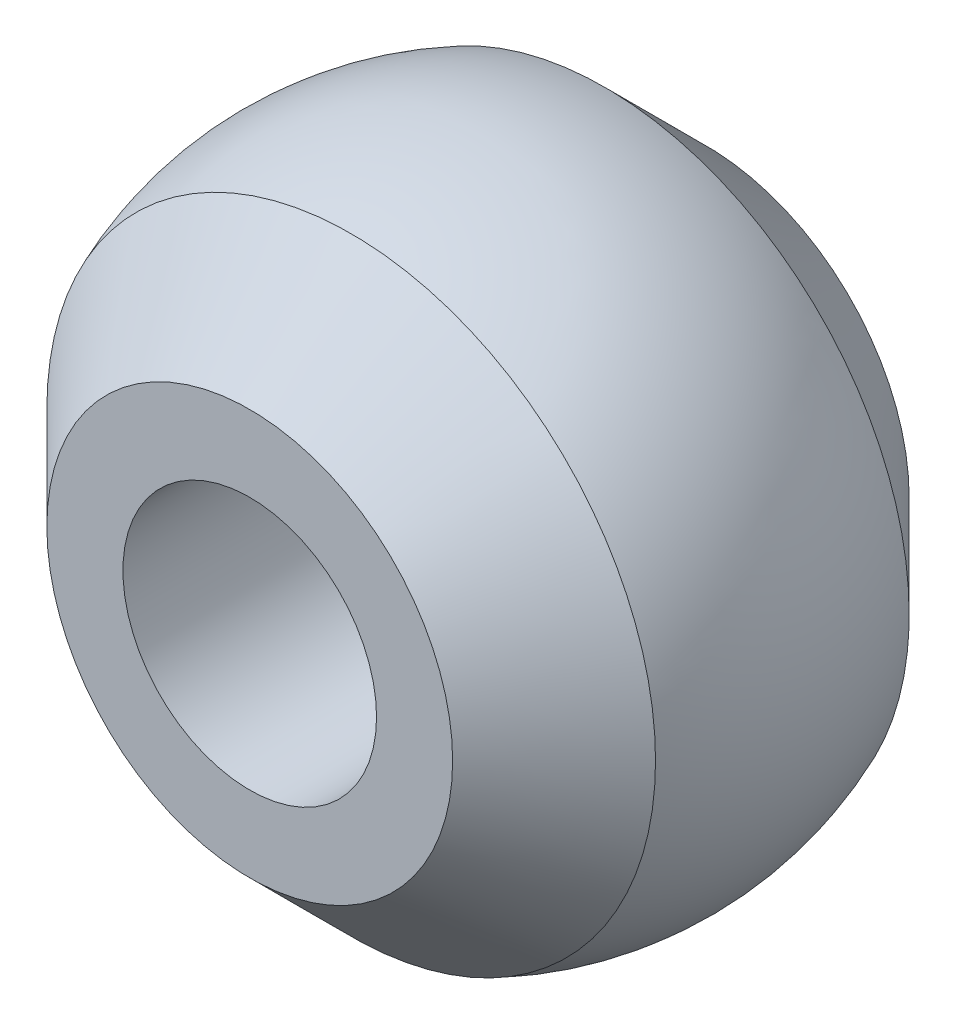
SolidWorks part; units mm, degrees
ref_plane "前视基准面" through (0, 0, 0) normal (0, 0, 1) x (1, 0, 0)
ref_plane "上视基准面" through (0, 0, 0) normal (0, 1, 0) x (1, 0, 0)
ref_plane "右视基准面" through (0, 0, 0) normal (1, 0, 0) x (0, 0, -1)
sketch "草图1" plane through (0, 0, 0) normal (0, 1, 0) x (1, 0, 0)
  circle A0 centre (0, 0) radius 10
  dimension "D1" = 20
extrude "凸台-拉伸1" add sketch "草图1" along normal blind 4.5
sketch "草图4" plane through (0, 0, 0) normal (0, 0, 1) x (1, 0, 0)
  line L0 (10, 4.5) -> (-10, 4.5) construction
  line L1 (-10, 4.5) -> (10, 4.5)
  line L2 (-10, 4.5) -> (-10, 14.5)
  line L4 (10, 4.5) -> (10, 14.5)
  line L5 (0, 193.283) -> (0, 138.3299) construction
  arc A0 (-10, 14.5) -> (10, 14.5) centre (0, 14.5) cw
  circle A1 centre (0, 14.5) radius 8
  dimension "D4" = 16
  dimension "D1" = 10
  dimension "D2" = 10
  dimension "D3" = 10
extrude "凸台-拉伸3" add sketch "草图4" against normal mid plane 10
sketch "草图5" plane through (0, 0, 0) normal (0, 0, 1) x (1, 0, 0)
  circle A0 centre (0, 14.5) radius 8
extrude "凸台-拉伸4" add sketch "草图5" along normal mid plane 5
ref_plane "基准面4" through (0, 0, 4.5) normal (0, 0, 1) x (1, 0, 0)
sketch "草图7" plane through (0, 0, 2.5) normal (0, 0, 1) x (1, 0, 0)
  circle A0 centre (0, 14.5) radius 6
  dimension "D1" = 12
sketch "草图8" plane through (0, 0, 4.5) normal (0, 0, 1) x (1, 0, 0)
  circle A0 centre (0, 14.5) radius 4
  dimension "D1" = 8
loft "放样1" add profiles "草图8", "草图7"
mirror "镜向1" about plane through (0, 0, 0) normal (0, 0, 1) of "放样1"
sketch "草图9" plane through (0, 4.5, 0) normal (0, 1, 0) x (1, 0, 0)
  circle A0 centre (0, 0) radius 10
  circle A1 centre (0, 0) radius 14.6272
extrude "切除-拉伸1" cut sketch "草图9" along normal blind 18
sketch "草图10" plane through (0, 0, 4.5) normal (0, 0, 1) x (1, 0, 0)
  circle A0 centre (0, 14.5) radius 2.5
  point P3 (0, 0)
  dimension "D1" = 5
extrude "切除-拉伸2" cut sketch "草图10" against normal blind 10
sketch "草图2" plane through (0, 0, 0) normal (0, -1, 0) x (1, 0, 0)
  circle A0 centre (0, 0) radius 6
  dimension "D2" = 12
extrude "凸台-拉伸5" add sketch "草图2" along normal blind 80 contours A0
sketch "草图11" plane through (0, 0, 4.5) normal (0, 0, 1) x (1, 0, 0)
  line L1 (-21.2182, 33.1182) -> (23.4246, 33.1182)
  line L2 (-21.2182, 33.1182) -> (-21.2182, -92.4529)
  line L3 (-21.2182, -92.4529) -> (23.4246, -92.4529)
  line L4 (23.4246, 33.1182) -> (23.4246, -92.4529)
  circle A0 centre (0, 14.5) radius 6
  dimension "D1" = 12
extrude "切除-拉伸3" cut sketch "草图11" against normal mid plane 36
sketch "草图13" plane through (0, 0, 0) normal (1, 0, 0) x (0, 0, -1)
  line L0 (-2.5, 20.5) -> (2.5, 20.5)
  line L1 (0, 14.5) -> (7.0594, 14.5) construction
  arc A0 (-2.5, 20.5) -> (2.5, 20.5) centre (0, 14.5) cw
  dimension "D1" = 6.5
revolve "旋转2" add sketch "草图13" angle 360 about L1
